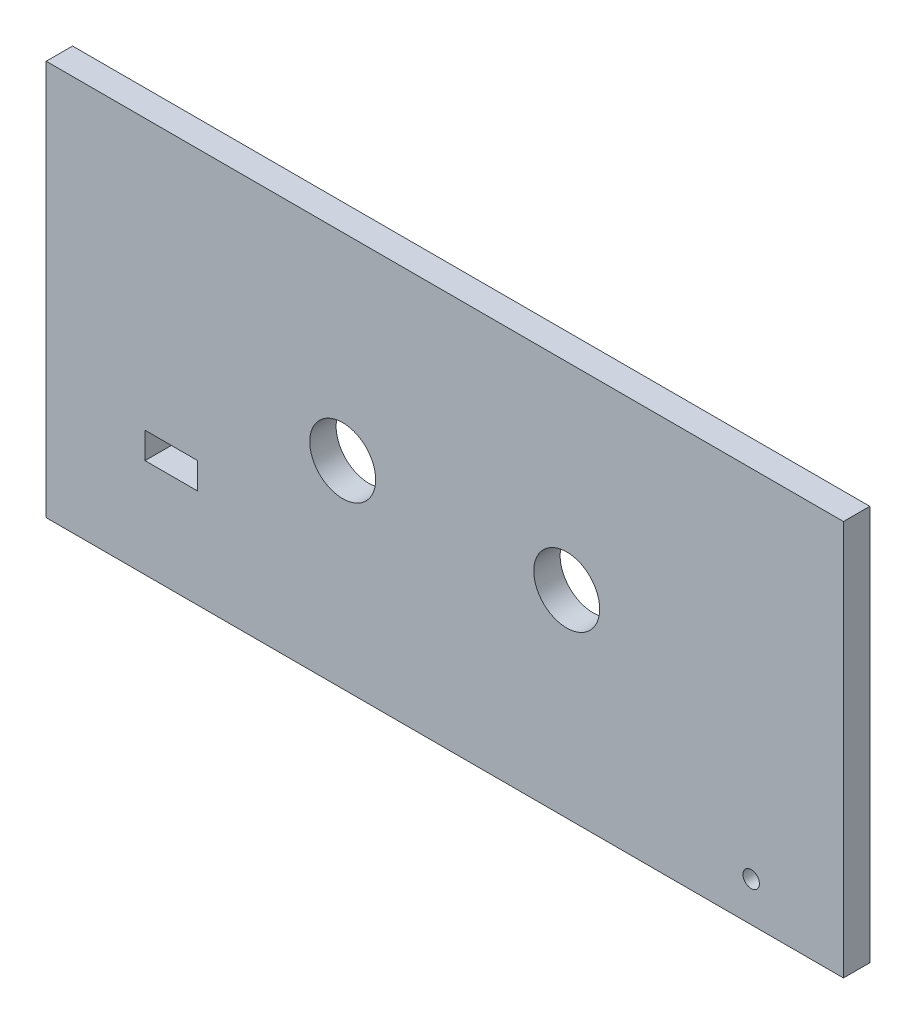
SolidWorks part; units mm, degrees
ref_plane "Front Plane" through (0, 0, 0) normal (0, 0, 1) x (1, 0, 0)
ref_plane "Top Plane" through (0, 0, 0) normal (0, 1, 0) x (1, 0, 0)
ref_plane "Right Plane" through (0, 0, 0) normal (1, 0, 0) x (0, 0, -1)
sketch "Sketch1" plane through (0, 0, 0) normal (0, 0, 1) x (1, 0, 0)
  line L1 (-79, -18.3961) -> (42, -18.3961)
  line L2 (-79, -18.3961) -> (-79, 41.6039)
  line L3 (-79, 41.6039) -> (42, 41.6039)
  line L4 (42, -18.3961) -> (42, 41.6039)
  line L5 (-64, 0.6039) -> (-56, 0.6039)
  line L6 (-64, 0.6039) -> (-64, -3.3961)
  line L7 (-64, -3.3961) -> (-56, -3.3961)
  line L8 (-56, 0.6039) -> (-56, -3.3961)
  circle A2 centre (-34, 11.6039) radius 5
  circle A3 centre (0, 11.6039) radius 5
  circle A4 centre (28, -12.3961) radius 1.25
  point P1 (0, 0)
  point P6 (-79, 11.6039)
  point P7 (42, 11.6039)
  dimension "D3" = 0
  dimension "D4" = 121
  dimension "D5" = 45
  dimension "D6" = 8
  dimension "D7" = 34
  dimension "D10" = 10
  dimension "D12" = 107
  dimension "D13" = 6
  dimension "D14" = 2.5
  dimension "D2" = 60
  dimension "D8" = 4
  dimension "D9" = 15
  dimension "D11" = 15
extrude "Boss-Extrude1" add sketch "Sketch1" along normal blind 4
